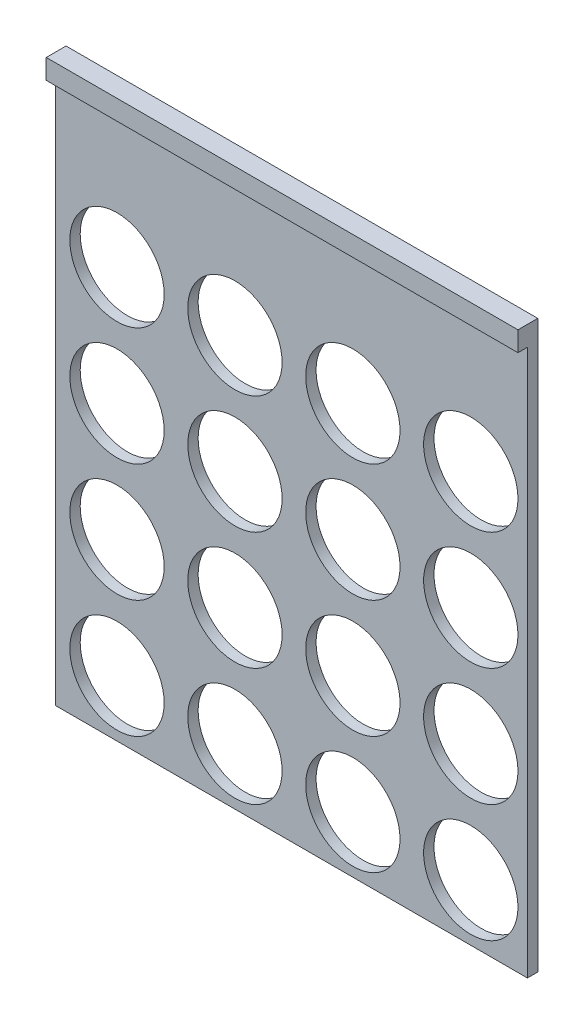
SolidWorks part; units mm, degrees
ref_plane "Ön Düzlem" through (0, 0, 0) normal (0, 0, 1) x (1, 0, 0)
ref_plane "Üst Düzlem" through (0, 0, 0) normal (0, 1, 0) x (1, 0, 0)
ref_plane "Sağ Düzlem" through (0, 0, 0) normal (1, 0, 0) x (0, 0, -1)
sketch "Sketch1" plane through (0, 0, 0) normal (0, 0, 1) x (1, 0, 0)
  line L0 (0, 0) -> (100, 0)
  line L1 (0, 0) -> (0, 120)
  line L2 (100, 0) -> (100, 120)
  line L3 (0, 120) -> (100, 120)
  dimension "D1" = 120
  dimension "D2" = 100
extrude "Boss-Extrude1" add sketch "Sketch1" along normal blind 2.2
sketch "Sketch2" plane through (0, 0, 2.2) normal (0, 0, 1) x (1, 0, 0)
  line L0 (100, 0) -> (100, 120) construction
  line L1 (0, 0) -> (100, 0) construction
  circle A0 centre (88, 12) radius 10
  circle A1 centre (63, 12) radius 10
  circle A2 centre (38, 12) radius 10
  circle A3 centre (13, 12) radius 10
  circle A4 centre (63, 37) radius 10
  circle A5 centre (38, 37) radius 10
  circle A6 centre (13, 37) radius 10
  circle A7 centre (63, 62) radius 10
  circle A8 centre (38, 62) radius 10
  circle A9 centre (13, 62) radius 10
  circle A10 centre (63, 87) radius 10
  circle A11 centre (38, 87) radius 10
  circle A12 centre (13, 87) radius 10
  circle A16 centre (88, 37) radius 10
  circle A17 centre (88, 62) radius 10
  circle A18 centre (88, 87) radius 10
  point P6 (108, 12)
  dimension "D1" = 20
  dimension "D2" = 12
  dimension "D3" = 12
  dimension "D4" = 4
  dimension "D5" = 4
extrude "Cut-Extrude1" cut sketch "Sketch2" against normal blind 10
sketch "Sketch3" plane through (0, 0, 2.2) normal (0, 0, 1) x (1, 0, 0)
  line L0 (0, 120) -> (100, 120)
  line L1 (0, 120) -> (0, 115.7944)
  line L2 (100, 120) -> (100, 115.7944)
  line L3 (0, 115.7944) -> (100, 115.7944)
extrude "Boss-Extrude2" add sketch "Sketch3" along normal blind 2
